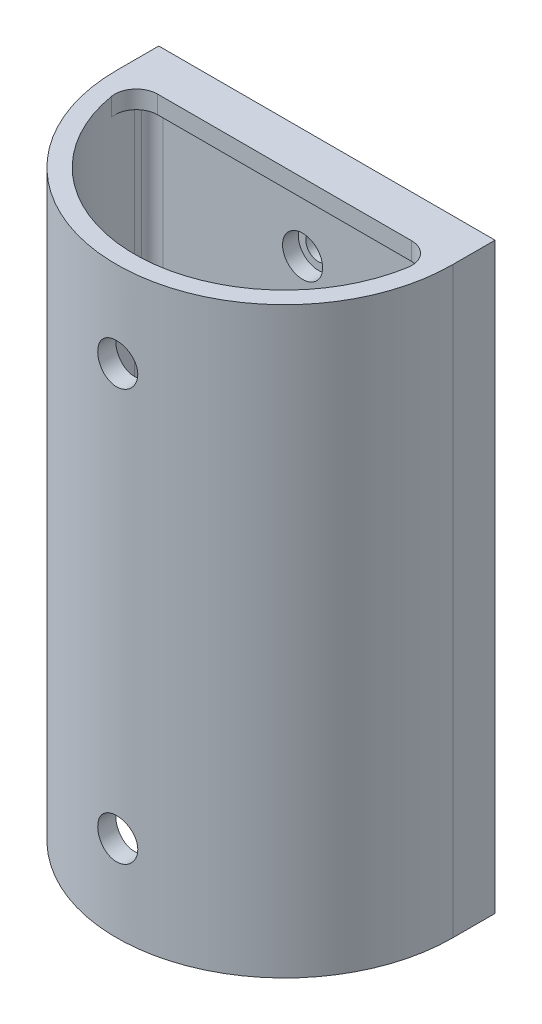
SolidWorks part; units mm, degrees
ref_plane "Front Plane" through (0, 0, 0) normal (0, 0, 1) x (1, 0, 0)
ref_plane "Top Plane" through (0, 0, 0) normal (0, 1, 0) x (1, 0, 0)
ref_plane "Right Plane" through (0, 0, 0) normal (1, 0, 0) x (0, 0, -1)
sketch "Sketch1" plane through (0, 0, 0) normal (0, 0, 1) x (1, 0, 0)
  line L0 (-23.5, 40.75) -> (23.5, 40.75)
  line L1 (-21, -38.25) -> (21, -38.25)
  line L2 (-21, -38.25) -> (-21, 38.25)
  line L3 (-21, 38.25) -> (21, 38.25)
  line L4 (21, -38.25) -> (21, 38.25)
  line L5 (-21, -38.25) -> (21, 38.25) construction
  line L6 (-21, 38.25) -> (21, -38.25) construction
  line L7 (23.5, -40.75) -> (23.5, 40.75)
  line L8 (-23.5, -40.75) -> (23.5, -40.75)
  line L9 (-23.5, -40.75) -> (-23.5, 40.75)
  line L10 (0, -28.75) -> (0, 28.75) construction
  circle A0 centre (0, 28.75) radius 1.75
  circle A1 centre (0, -28.75) radius 1.75
  point P0 (0, 0)
  point P13 (0, 0)
  dimension "D5" = 3.5
  dimension "D6" = 3.5
  dimension "D1" = 76.5
  dimension "D2" = 42
  dimension "D4" = 12
  dimension "D3" = 2.5
extrude "Boss-Extrude1" add sketch "Sketch1" along normal blind 3.4 contours L9 L8 L7 L0 L4 L1 L2 L3 | A1 | A0
sketch "Sketch2" plane through (0, 0, 3.4) normal (0, 0, 1) x (1, 0, 0)
  circle A0 centre (0, 28.75) radius 2.8
  circle A1 centre (0, -28.75) radius 2.8
  dimension "D1" = 5.6
  dimension "D2" = 5.6
extrude "Cut-Extrude1" cut sketch "Sketch2" against normal blind 2.2
sketch "Sketch3" plane through (0, 0, 3.4) normal (0, 0, 1) x (1, 0, 0)
  line L0 (21, -38.25) -> (21, 38.25) construction
  line L1 (23.5, -40.75) -> (23.5, 40.75) construction
  line L2 (-23.5, 40.75) -> (23.5, 40.75) construction
  line L3 (-21, 38.25) -> (21, 38.25) construction
  line L4 (-21, -38.25) -> (-21, 38.25) construction
  line L5 (-23.5, -40.75) -> (-23.5, 40.75) construction
  line L6 (21, -38.25) -> (21, 38.25)
  line L7 (23.5, -40.75) -> (23.5, 40.75)
  line L8 (-23.5, 40.75) -> (23.5, 40.75)
  line L9 (-21, 38.25) -> (21, 38.25)
  line L10 (-21, -38.25) -> (-21, 38.25)
  line L11 (-23.5, -40.75) -> (-23.5, 40.75)
  line L12 (-21, -38.25) -> (-21, -40.75)
  line L13 (-23.5, -40.75) -> (23.5, -40.75) construction
  line L14 (-23.5, -40.75) -> (-21, -40.75)
  line L15 (21, -38.25) -> (21, -40.75)
  line L16 (21, -40.75) -> (23.5, -40.75)
extrude "Boss-Extrude2" add sketch "Sketch3" along normal blind 2.5
sketch "Sketch4" plane through (0, 40.75, 0) normal (0, 1, 0) x (1, 0, 0)
  line L0 (23.5, -5.9) -> (-23.5, -5.9) construction
  line L1 (23.5, -5.9) -> (23.5, 0) construction
  line L2 (23.5, -5.9) -> (21, -5.9)
  line L3 (-21, -5.9) -> (-23.5, -5.9)
  arc A0 (-23.5, -5.9) -> (23.5, -5.9) centre (0, -5.9) ccw
  arc A1 (-21, -5.9) -> (21, -5.9) centre (0, -5.9) ccw
  dimension "D1" = 2.5
extrude "Boss-Extrude3" add sketch "Sketch4" against normal up to surface (81.5 mm away) up to face at (0, -40.75, 3.8)
sketch "Sketch5" plane through (0, 0, 3.4) normal (0, 0, 1) x (1, 0, 0)
  circle A0 centre (0, -28.75) radius 2.8 construction
  circle A1 centre (0, -28.75) radius 2.8
  circle A2 centre (0, 28.75) radius 2.8 construction
  circle A3 centre (0, 28.75) radius 2.8
extrude "Cut-Extrude2" cut sketch "Sketch5" along normal through all
fillet "Fillet1" radius 3 2 edges at (-21, 39.5, 5.9) (21, 39.5, 5.9)
fillet "Fillet2" radius 1.5 3 edges at (0, 38.25, 3.4) (21, -1.25, 3.4) (-21, -1.25, 3.4)
